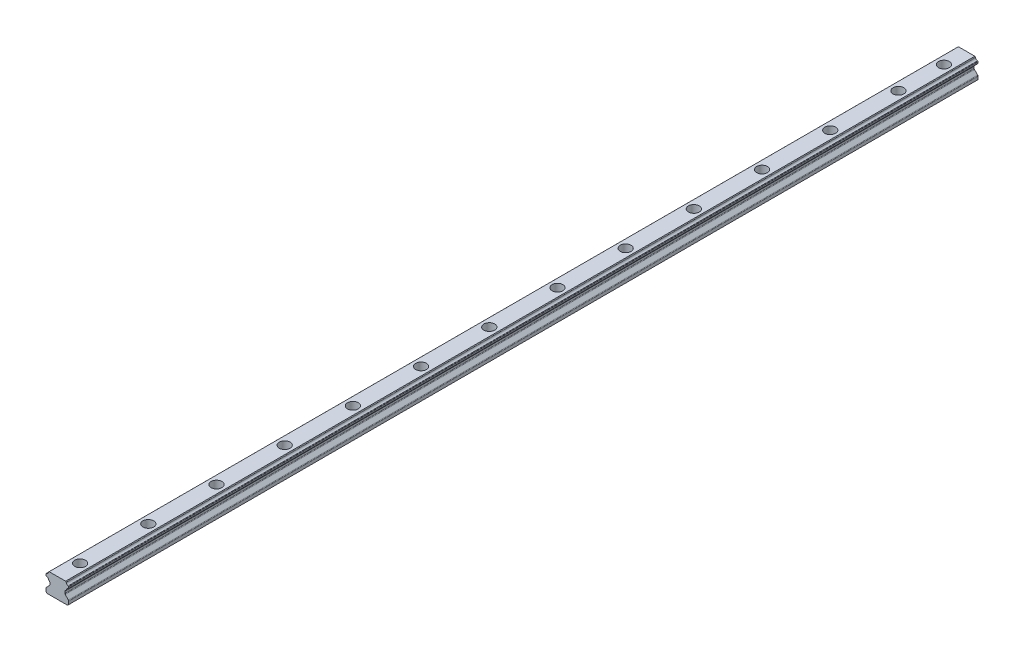
SolidWorks part; units mm, degrees
material "Stainless Steel (ferritic)"
ref_plane "Front Plane" through (0, 0, 0) normal (0, 0, 1) x (1, 0, 0)
ref_plane "Top Plane" through (0, 0, 0) normal (0, 1, 0) x (1, 0, 0)
ref_plane "Right Plane" through (0, 0, 0) normal (1, 0, 0) x (0, 0, -1)
sketch "Sketch10" plane through (0, 0, 0) normal (0, 0, 1) x (1, 0, 0)
  line L0 (-10, -10.3385) -> (-10, -13)
  line L1 (-10, -13) -> (-9, -14)
  line L2 (-9, -14) -> (9, -14)
  line L3 (6.8929, -6.8172) -> (9.7071, -9.6314)
  line L4 (6.6, -4.5499) -> (6.6, -6.1101)
  line L5 (7.6302, -3.1056) -> (6.8929, -3.8428)
  line L6 (9.8536, -0.8822) -> (9.6906, -1.0451)
  line L7 (10, 0.5286) -> (10, -0.5286)
  line L8 (9.6906, 1.0451) -> (9.8536, 0.8822)
  line L9 (7.2357, 3.5) -> (7.6325, 3.1032)
  line L10 (10, -13) -> (9, -14)
  line L11 (10, -10.3385) -> (10, -13)
  line L12 (7.2357, 3.5) -> (-7.2357, 3.5)
  line L13 (-7.2357, 3.5) -> (-7.6325, 3.1032)
  line L14 (-9.6906, 1.0451) -> (-9.8536, 0.8822)
  line L15 (-10, 0.5286) -> (-10, -0.5286)
  line L16 (-9.8536, -0.8822) -> (-9.6906, -1.0451)
  line L17 (-7.6302, -3.1056) -> (-6.8929, -3.8428)
  line L18 (-6.6, -4.5499) -> (-6.6, -6.1101)
  line L19 (-6.8929, -6.8172) -> (-9.7071, -9.6314)
  line L20 (0, -14) -> (0, 3.5) construction
  line L21 (-10, 0) -> (0, 0) construction
  arc A0 (-9.7071, -9.6314) -> (-10, -10.3385) centre (-9, -10.3385) ccw
  arc A1 (6.8929, -6.8172) -> (6.6, -6.1101) centre (7.6, -6.1101) cw
  arc A2 (6.6, -4.5499) -> (6.8929, -3.8428) centre (7.6, -4.5499) cw
  arc A3 (7.8468, -2.7675) -> (7.6302, -3.1056) centre (7.3529, -2.6895) cw
  arc A4 (7.8468, -2.7675) -> (9.4318, -1.1825) centre (9.8106, -3.1463) cw
  arc A5 (9.6906, -1.0451) -> (9.4318, -1.1825) centre (9.3371, -0.6915) cw
  arc A6 (10, -0.5286) -> (9.8536, -0.8822) centre (9.5, -0.5286) cw
  arc A7 (9.8536, 0.8822) -> (10, 0.5286) centre (9.5, 0.5286) cw
  arc A8 (9.4224, 1.1941) -> (9.6906, 1.0451) centre (9.3254, 0.7036) cw
  arc A9 (9.4224, 1.1941) -> (7.8482, 2.768) centre (9.8101, 3.1561) cw
  arc A10 (7.6325, 3.1032) -> (7.8482, 2.768) centre (7.3547, 2.6875) cw
  arc A11 (9.7071, -9.6314) -> (10, -10.3385) centre (9, -10.3385) cw
  arc A12 (-7.6325, 3.1032) -> (-7.8482, 2.768) centre (-7.3547, 2.6875) ccw
  arc A13 (-9.4224, 1.1941) -> (-7.8482, 2.768) centre (-9.8101, 3.1561) ccw
  arc A14 (-9.4224, 1.1941) -> (-9.6906, 1.0451) centre (-9.3254, 0.7036) ccw
  arc A15 (-9.8536, 0.8822) -> (-10, 0.5286) centre (-9.5, 0.5286) ccw
  arc A16 (-10, -0.5286) -> (-9.8536, -0.8822) centre (-9.5, -0.5286) ccw
  arc A17 (-9.6906, -1.0451) -> (-9.4318, -1.1825) centre (-9.3371, -0.6915) ccw
  arc A18 (-7.8468, -2.7675) -> (-9.4318, -1.1825) centre (-9.8106, -3.1463) ccw
  arc A19 (-7.8468, -2.7675) -> (-7.6302, -3.1056) centre (-7.3529, -2.6895) ccw
  arc A20 (-6.6, -4.5499) -> (-6.8929, -3.8428) centre (-7.6, -4.5499) ccw
  arc A21 (-6.8929, -6.8172) -> (-6.6, -6.1101) centre (-7.6, -6.1101) ccw
  dimension "D3" = 17.5
  dimension "D4" = 135
  dimension "D1" = 3.5
  dimension "D2" = 1
  dimension "D5" = 14
extrude "BODY" add sketch "Sketch10" along normal mid plane 800
hole_wizard "CBORE for M6 SHCS1" positions "Sketch12" profile "Sketch11" counterbore size "M6" standard "ANSI Metric"
sketch "Sketch12" plane through (0, 3.5, 0) normal (0, 1, 0) x (1, 0, 0)
  line L0 (0, -400) -> (0, -380) construction
  line L2 (7.2357, -400) -> (-7.2357, -400) construction
  point P0 (0, -380)
  dimension "D1" = 20
sketch "Sketch11" plane through (0, 3.5, 380) normal (1, 0, 0) x (0, 0, 1)
  line L0 (0, 0) -> (0, 17.5)
  line L1 (0, 17.5) -> (3, 17.5)
  line L3 (3, 17.5) -> (3, 8.4)
  line L4 (3, 8.4) -> (4.75, 8.4)
  line L5 (4.75, 8.4) -> (4.75, 0)
  line L7 (4.75, 0) -> (0, 0)
  line L11 (0, -6.35) -> (0, 107.95) construction
  dimension "Thru Hole Dia." = 6
  dimension "Thru Hole Depth" = 17.5
  dimension "C'Bore Dia." = 9.5
  dimension "C'Bore Depth" = 8.4
mirror "MIRROR FIRST COUNTERBORE" about plane through (0, 0, 0) normal (0, 0, 1) of "CBORE for M6 SHCS1"
sketch "END TO END HOLES" plane through (0, 0, 0) normal (0, 1, 0) x (1, 0, 0)
  line L0 (0, -380) -> (0, 380) construction
pattern_linear "LP CBORE" count 13 spacing 60 along (0, 0, -1) of "CBORE for M6 SHCS1"
equation "\"D1@LP CBORE\"      = INT(\"DISTANCE@END TO END HOLES\"/60)+1"
